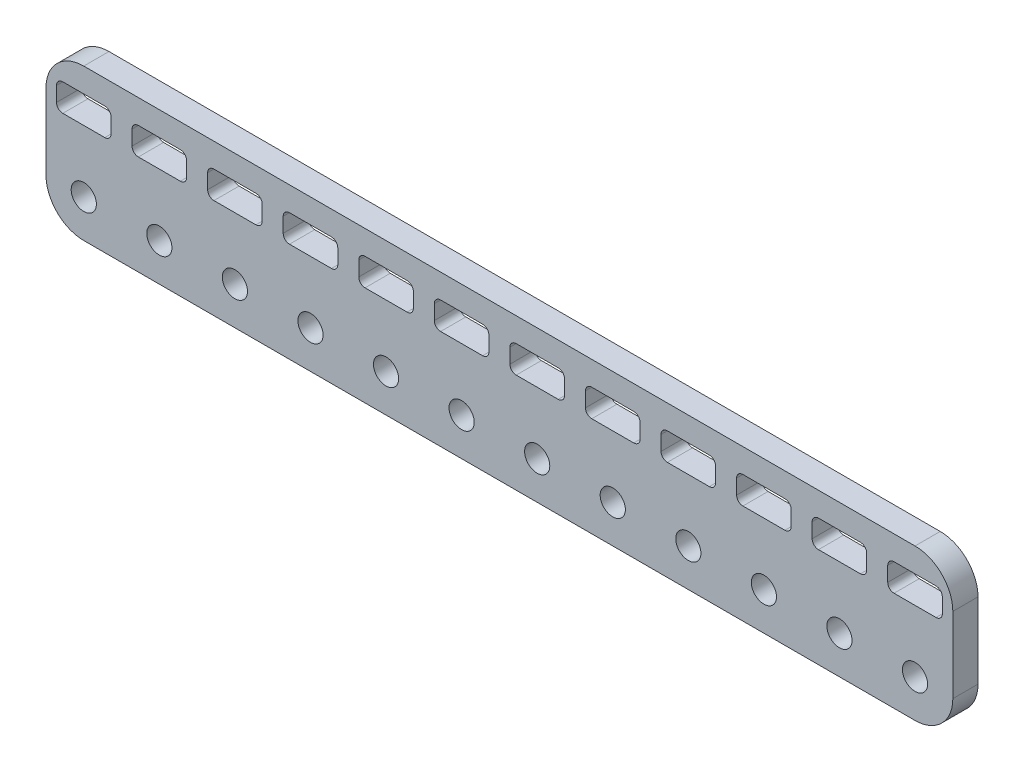
SolidWorks part; units mm, degrees
ref_plane "Alzado" through (0, 0, 0) normal (0, 0, 1) x (1, 0, 0)
ref_plane "Planta" through (0, 0, 0) normal (0, 1, 0) x (1, 0, 0)
ref_plane "Vista lateral" through (0, 0, 0) normal (1, 0, 0) x (0, 0, -1)
sketch "Model" plane through (0, 0, 0) normal (0, 0, 1) x (1, 0, 0)
  line L0 (256.4291, 228.7422) -> (355.4291, 228.7422)
  line L1 (355.4291, 210.7422) -> (256.4291, 210.7422)
  line L2 (359.9291, 224.2422) -> (359.9291, 215.2422)
  line L3 (251.9291, 224.2422) -> (251.9291, 215.2422)
  line L4 (267.9291, 222.6172) -> (262.9291, 222.6172)
  line L5 (262.1791, 223.3672) -> (262.1791, 225.1172)
  line L6 (262.9291, 225.8672) -> (267.9291, 225.8672)
  line L7 (268.6791, 225.1172) -> (268.6791, 223.3672)
  line L8 (285.9291, 222.6172) -> (280.9291, 222.6172)
  line L9 (280.1791, 223.3672) -> (280.1791, 225.1172)
  line L10 (280.9291, 225.8672) -> (285.9291, 225.8672)
  line L11 (286.6791, 225.1172) -> (286.6791, 223.3672)
  line L12 (258.9291, 222.6172) -> (253.9291, 222.6172)
  line L13 (253.1791, 223.3672) -> (253.1791, 225.1172)
  line L14 (253.9291, 225.8672) -> (258.9291, 225.8672)
  line L15 (259.6791, 225.1172) -> (259.6791, 223.3672)
  line L16 (276.9291, 222.6172) -> (271.9291, 222.6172)
  line L17 (271.1791, 223.3672) -> (271.1791, 225.1172)
  line L18 (271.9291, 225.8672) -> (276.9291, 225.8672)
  line L19 (277.6791, 225.1172) -> (277.6791, 223.3672)
  line L20 (294.9291, 222.6172) -> (289.9291, 222.6172)
  line L21 (289.1791, 223.3672) -> (289.1791, 225.1172)
  line L22 (289.9291, 225.8672) -> (294.9291, 225.8672)
  line L23 (295.6791, 225.1172) -> (295.6791, 223.3672)
  line L24 (303.9291, 222.6172) -> (298.9291, 222.6172)
  line L25 (298.1791, 223.3672) -> (298.1791, 225.1172)
  line L26 (298.9291, 225.8672) -> (303.9291, 225.8672)
  line L27 (304.6791, 225.1172) -> (304.6791, 223.3672)
  line L28 (321.9291, 222.6172) -> (316.9291, 222.6172)
  line L29 (316.1791, 223.3672) -> (316.1791, 225.1172)
  line L30 (316.9291, 225.8672) -> (321.9291, 225.8672)
  line L31 (322.6791, 225.1172) -> (322.6791, 223.3672)
  line L32 (312.9291, 222.6172) -> (307.9291, 222.6172)
  line L33 (307.1791, 223.3672) -> (307.1791, 225.1172)
  line L34 (307.9291, 225.8672) -> (312.9291, 225.8672)
  line L35 (313.6791, 225.1172) -> (313.6791, 223.3672)
  line L36 (357.9291, 222.6172) -> (352.9291, 222.6172)
  line L37 (352.1791, 223.3672) -> (352.1791, 225.1172)
  line L38 (352.9291, 225.8672) -> (357.9291, 225.8672)
  line L39 (358.6791, 225.1172) -> (358.6791, 223.3672)
  line L40 (348.9291, 222.6172) -> (343.9291, 222.6172)
  line L41 (343.1791, 223.3672) -> (343.1791, 225.1172)
  line L42 (343.9291, 225.8672) -> (348.9291, 225.8672)
  line L43 (349.6791, 225.1172) -> (349.6791, 223.3672)
  line L44 (339.9291, 222.6172) -> (334.9291, 222.6172)
  line L45 (334.1791, 223.3672) -> (334.1791, 225.1172)
  line L46 (334.9291, 225.8672) -> (339.9291, 225.8672)
  line L47 (340.6791, 225.1172) -> (340.6791, 223.3672)
  line L48 (330.9291, 222.6172) -> (325.9291, 222.6172)
  line L49 (325.1791, 223.3672) -> (325.1791, 225.1172)
  line L50 (325.9291, 225.8672) -> (330.9291, 225.8672)
  line L51 (331.6791, 225.1172) -> (331.6791, 223.3672)
  arc A0 (359.9291, 224.2422) -> (355.4291, 228.7422) centre (355.4291, 224.2422) ccw
  arc A1 (256.4291, 228.7422) -> (251.9291, 224.2422) centre (256.4291, 224.2422) ccw
  arc A2 (251.9291, 215.2422) -> (256.4291, 210.7422) centre (256.4291, 215.2422) ccw
  arc A3 (355.4291, 210.7422) -> (359.9291, 215.2422) centre (355.4291, 215.2422) ccw
  circle A4 centre (337.4291, 215.2422) radius 1.5
  circle A5 centre (319.4291, 215.2422) radius 1.5
  circle A6 centre (328.4291, 215.2422) radius 1.5
  circle A7 centre (310.4291, 215.2422) radius 1.5
  circle A8 centre (292.4291, 215.2422) radius 1.5
  circle A9 centre (301.4291, 215.2422) radius 1.5
  circle A10 centre (274.4291, 215.2422) radius 1.5
  circle A11 centre (283.4291, 215.2422) radius 1.5
  circle A12 centre (265.4291, 215.2422) radius 1.5
  circle A13 centre (256.4291, 215.2422) radius 1.5
  circle A14 centre (346.4291, 215.2422) radius 1.5
  circle A15 centre (355.4291, 215.2422) radius 1.5
  arc A16 (262.1791, 223.3672) -> (262.9291, 222.6172) centre (262.9291, 223.3672) ccw
  arc A17 (262.9291, 225.8672) -> (262.1791, 225.1172) centre (262.9291, 225.1172) ccw
  arc A18 (268.6791, 225.1172) -> (267.9291, 225.8672) centre (267.9291, 225.1172) ccw
  arc A19 (267.9291, 222.6172) -> (268.6791, 223.3672) centre (267.9291, 223.3672) ccw
  arc A20 (280.1791, 223.3672) -> (280.9291, 222.6172) centre (280.9291, 223.3672) ccw
  arc A21 (280.9291, 225.8672) -> (280.1791, 225.1172) centre (280.9291, 225.1172) ccw
  arc A22 (286.6791, 225.1172) -> (285.9291, 225.8672) centre (285.9291, 225.1172) ccw
  arc A23 (285.9291, 222.6172) -> (286.6791, 223.3672) centre (285.9291, 223.3672) ccw
  arc A24 (253.1791, 223.3672) -> (253.9291, 222.6172) centre (253.9291, 223.3672) ccw
  arc A25 (253.9291, 225.8672) -> (253.1791, 225.1172) centre (253.9291, 225.1172) ccw
  arc A26 (259.6791, 225.1172) -> (258.9291, 225.8672) centre (258.9291, 225.1172) ccw
  arc A27 (258.9291, 222.6172) -> (259.6791, 223.3672) centre (258.9291, 223.3672) ccw
  arc A28 (271.1791, 223.3672) -> (271.9291, 222.6172) centre (271.9291, 223.3672) ccw
  arc A29 (271.9291, 225.8672) -> (271.1791, 225.1172) centre (271.9291, 225.1172) ccw
  arc A30 (277.6791, 225.1172) -> (276.9291, 225.8672) centre (276.9291, 225.1172) ccw
  arc A31 (276.9291, 222.6172) -> (277.6791, 223.3672) centre (276.9291, 223.3672) ccw
  arc A32 (289.1791, 223.3672) -> (289.9291, 222.6172) centre (289.9291, 223.3672) ccw
  arc A33 (289.9291, 225.8672) -> (289.1791, 225.1172) centre (289.9291, 225.1172) ccw
  arc A34 (295.6791, 225.1172) -> (294.9291, 225.8672) centre (294.9291, 225.1172) ccw
  arc A35 (294.9291, 222.6172) -> (295.6791, 223.3672) centre (294.9291, 223.3672) ccw
  arc A36 (298.1791, 223.3672) -> (298.9291, 222.6172) centre (298.9291, 223.3672) ccw
  arc A37 (298.9291, 225.8672) -> (298.1791, 225.1172) centre (298.9291, 225.1172) ccw
  arc A38 (304.6791, 225.1172) -> (303.9291, 225.8672) centre (303.9291, 225.1172) ccw
  arc A39 (303.9291, 222.6172) -> (304.6791, 223.3672) centre (303.9291, 223.3672) ccw
  arc A40 (316.1791, 223.3672) -> (316.9291, 222.6172) centre (316.9291, 223.3672) ccw
  arc A41 (316.9291, 225.8672) -> (316.1791, 225.1172) centre (316.9291, 225.1172) ccw
  arc A42 (322.6791, 225.1172) -> (321.9291, 225.8672) centre (321.9291, 225.1172) ccw
  arc A43 (321.9291, 222.6172) -> (322.6791, 223.3672) centre (321.9291, 223.3672) ccw
  arc A44 (307.1791, 223.3672) -> (307.9291, 222.6172) centre (307.9291, 223.3672) ccw
  arc A45 (307.9291, 225.8672) -> (307.1791, 225.1172) centre (307.9291, 225.1172) ccw
  arc A46 (313.6791, 225.1172) -> (312.9291, 225.8672) centre (312.9291, 225.1172) ccw
  arc A47 (312.9291, 222.6172) -> (313.6791, 223.3672) centre (312.9291, 223.3672) ccw
  arc A48 (352.1791, 223.3672) -> (352.9291, 222.6172) centre (352.9291, 223.3672) ccw
  arc A49 (352.9291, 225.8672) -> (352.1791, 225.1172) centre (352.9291, 225.1172) ccw
  arc A50 (358.6791, 225.1172) -> (357.9291, 225.8672) centre (357.9291, 225.1172) ccw
  arc A51 (357.9291, 222.6172) -> (358.6791, 223.3672) centre (357.9291, 223.3672) ccw
  arc A52 (343.1791, 223.3672) -> (343.9291, 222.6172) centre (343.9291, 223.3672) ccw
  arc A53 (343.9291, 225.8672) -> (343.1791, 225.1172) centre (343.9291, 225.1172) ccw
  arc A54 (349.6791, 225.1172) -> (348.9291, 225.8672) centre (348.9291, 225.1172) ccw
  arc A55 (348.9291, 222.6172) -> (349.6791, 223.3672) centre (348.9291, 223.3672) ccw
  arc A56 (334.1791, 223.3672) -> (334.9291, 222.6172) centre (334.9291, 223.3672) ccw
  arc A57 (334.9291, 225.8672) -> (334.1791, 225.1172) centre (334.9291, 225.1172) ccw
  arc A58 (340.6791, 225.1172) -> (339.9291, 225.8672) centre (339.9291, 225.1172) ccw
  arc A59 (339.9291, 222.6172) -> (340.6791, 223.3672) centre (339.9291, 223.3672) ccw
  arc A60 (325.1791, 223.3672) -> (325.9291, 222.6172) centre (325.9291, 223.3672) ccw
  arc A61 (325.9291, 225.8672) -> (325.1791, 225.1172) centre (325.9291, 225.1172) ccw
  arc A62 (331.6791, 225.1172) -> (330.9291, 225.8672) centre (330.9291, 225.1172) ccw
  arc A63 (330.9291, 222.6172) -> (331.6791, 223.3672) centre (330.9291, 223.3672) ccw
extrude "Saliente-Extruir1" add sketch "Model" along normal blind 3
